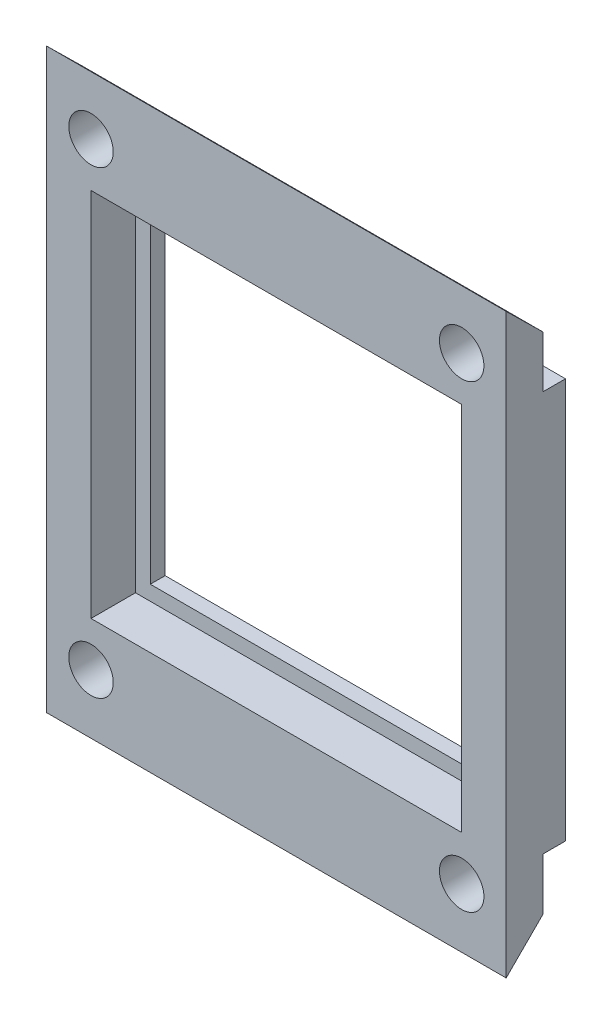
SolidWorks part; units mm, degrees
ref_plane "Front Plane" through (0, 0, 0) normal (0, 0, 1) x (1, 0, 0)
ref_plane "Top Plane" through (0, 0, 0) normal (0, 1, 0) x (1, 0, 0)
ref_plane "Right Plane" through (0, 0, 0) normal (1, 0, 0) x (0, 0, -1)
sketch "Sketch3" plane through (0, 0, 0) normal (0, 0, 1) x (1, 0, 0)
  line L1 (-15.5, -15.5) -> (15.5, -15.5)
  line L2 (-15.5, -15.5) -> (-15.5, 15.5)
  line L3 (-15.5, 15.5) -> (15.5, 15.5)
  line L4 (15.5, -15.5) -> (15.5, 15.5)
  line L5 (-15.5, -15.5) -> (15.5, 15.5) construction
  line L6 (-15.5, 15.5) -> (15.5, -15.5) construction
  point P0 (0, 0)
  dimension "D1" = 31
  dimension "D2" = 31
extrude "Boss-Extrude2" add sketch "Sketch3" along normal blind 4
sketch "Sketch4" plane through (0, 0, 4) normal (0, 0, 1) x (1, 0, 0)
  line L1 (-12.5, -12.5) -> (12.5, -12.5)
  line L2 (-12.5, -12.5) -> (-12.5, 12.5)
  line L3 (-12.5, 12.5) -> (12.5, 12.5)
  line L4 (12.5, -12.5) -> (12.5, 12.5)
  line L5 (-12.5, -12.5) -> (12.5, 12.5) construction
  line L6 (-12.5, 12.5) -> (12.5, -12.5) construction
  point P0 (0, 0)
  dimension "D1" = 25
  dimension "D2" = 25
extrude "Cut-Extrude1" cut sketch "Sketch4" against normal blind 3
sketch "Sketch5" plane through (0, 0, 1) normal (0, 0, 1) x (1, 0, 0)
  line L1 (-11.5, -11.5) -> (11.5, -11.5)
  line L2 (-11.5, -11.5) -> (-11.5, 11.5)
  line L3 (-11.5, 11.5) -> (11.5, 11.5)
  line L4 (11.5, -11.5) -> (11.5, 11.5)
  line L5 (-11.5, -11.5) -> (11.5, 11.5) construction
  line L6 (-11.5, 11.5) -> (11.5, -11.5) construction
  point P0 (0, 0)
  dimension "D1" = 23
  dimension "D2" = 23
extrude "Cut-Extrude2" cut sketch "Sketch5" against normal blind 5
sketch "Sketch6" plane through (-15.5, 0, 0) normal (-1, 0, 0) x (0, 0, 1)
  line L0 (4, -15.5) -> (4, -19.5)
  line L1 (4, -19.5) -> (0, -15.5)
  line L2 (0, -15.5) -> (4, -15.5)
sweep "Sweep1" add profiles "Sketch6" path edge at (0, -15.5, 4)
sketch "Sketch8" plane through (-15.5, 0, 0) normal (-1, 0, 0) x (0, 0, 1)
  line L0 (0, 15.5) -> (4, 19.4363)
  line L1 (0, 15.5) -> (0, -15.5) construction
  line L2 (4, 15.5) -> (0, 15.5) construction
  line L3 (4, 19.4363) -> (4, 15.5)
  line L4 (4, 15.5) -> (4, -19.5) construction
  line L5 (4, 15.5) -> (0, 15.5)
sweep "Sweep2" add profiles "Sketch8" path edge at (0, 15.5, 0)
sketch "Sketch9" plane through (0, 0, 0) normal (0, 0, -1) x (-1, 0, 0)
  line L0 (-15.5, 15.5) -> (15.5, 15.5) construction
  line L1 (-15.5, -15.5) -> (-15.5, 15.5) construction
  circle A0 centre (-12.5, 15.5) radius 1.5
  dimension "D1" = 3
  dimension "D2" = 3
extrude "Cut-Extrude3" cut sketch "Sketch9" against normal blind 10
mirror "Mirror1" about plane through (0, 0, 0) normal (1, 0, 0) of "Cut-Extrude3"
mirror "Mirror3" about plane through (0, 0, 0) normal (0, 1, 0) of "Mirror1", "Cut-Extrude3"
sketch "Sketch10" plane through (-15.5, 0, 0) normal (-1, 0, 0) x (0, 0, 1)
  line L0 (0, -15.5) -> (4, -19.5) construction
  line L1 (0, 15.5) -> (0, -15.5) construction
  line L2 (0, -15.5) -> (1.5, -17)
  line L3 (0, -13.5) -> (0, -15.5)
  line L4 (0, -15.5) -> (1.5, -17) construction
  line L5 (0, -15.5) -> (1.5, -17)
  line L6 (1.5, -17) -> (0, -13.5) construction
  line L7 (0, -14) -> (0, -15.5) construction
  line L8 (0, -14) -> (0, -15.5)
  line L9 (4, 19.4363) -> (0, 15.5) construction
  line L11 (1.5243, 17) -> (0, 15.5)
  line L14 (1.5243, 17) -> (0, 15.5) construction
  line L16 (1.5243, 17) -> (0, 15.5)
  line L19 (0, -14) -> (0, -15.5)
  line L20 (0, 13.5) -> (1.5243, 17) construction
  line L21 (1.5, -17) -> (1.5, -13.5)
  line L22 (1.5, -13.5) -> (0, -13.5)
  line L23 (1.5243, 17) -> (1.5243, 13.5)
  line L24 (1.5243, 13.5) -> (0, 13.5)
  line L25 (0, 15.5) -> (0, 13.5)
  line M4 (0, 15.5) -> (0, -15.5)
  line M5 (0, -15.5) -> (4, -19.5)
  line M7 (4, 19.4363) -> (0, 15.5)
  dimension "D1" = 2
  dimension "D2" = 2
extrude "Cut-Extrude4" cut sketch "Sketch10" against normal through all contours L6 M5 M4 | L20 M4 M7
